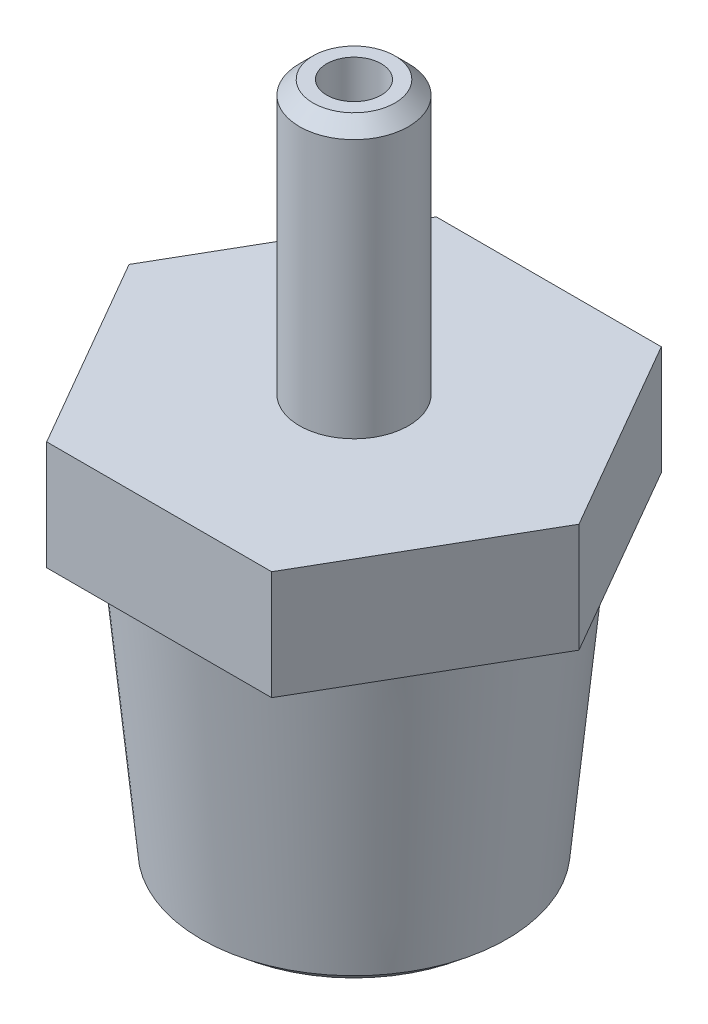
SolidWorks part; units mm, degrees
material "Brass"
ref_plane "Ground_Plane" through (0, 0, 0) normal (0, 0, 1) x (1, 0, 0)
ref_plane "VehicleCentre_Plane" through (0, 0, 0) normal (0, 1, 0) x (1, 0, 0)
ref_plane "FrontAxle_Plane" through (0, 0, 0) normal (1, 0, 0) x (0, 0, -1)
sketch "Sketch1" plane through (0, 0, 0) normal (0, 0, 1) x (1, 0, 0)
  line L0 (1, 25) -> (2, 25)
  line L1 (2, 25) -> (2, 15)
  line L2 (2, 15) -> (7, 15)
  line L3 (7, 15) -> (5.5562, 0)
  line L4 (5.5562, 0) -> (3.5562, 0)
  line L5 (3.5562, 0) -> (3.5562, 12)
  line L6 (3.5562, 12) -> (1, 12)
  line L7 (1, 12) -> (1, 25)
  line L8 (0, 0) -> (0, 25) construction
  dimension "D1" = 1
  dimension "D2" = 25
  dimension "D3" = 15
  dimension "D4" = 5.5562
  dimension "D5" = 7
  dimension "D6" = 2
  dimension "D7" = 12
  dimension "D8" = 2
revolve "Revolve1" add sketch "Sketch1" angle 360 about L8
sketch "Sketch2" plane through (0, 15, 0) normal (0, 1, 0) x (1, 0, 0)
  line L1 (-8.2489, 0) -> (-4.1244, -7.1437)
  line L2 (-4.1244, -7.1437) -> (4.1244, -7.1437)
  line L3 (4.1244, -7.1437) -> (8.2489, 0)
  line L4 (8.2489, 0) -> (4.1244, 7.1437)
  line L5 (4.1244, 7.1437) -> (-4.1244, 7.1437)
  line L6 (-4.1244, 7.1437) -> (-8.2489, 0)
  circle A0 centre (0, 0) radius 7.1437 construction
  circle A2 centre (0, 0) radius 1 construction
  circle A3 centre (0, 0) radius 1
  dimension "D1" = 14.2875
extrude "Boss-Extrude1" add sketch "Sketch2" against normal blind 4
chamfer "Chamfer1" distance 0.5 angle 45 2 edges at (0, 0, -5.5562) (0, 25, -2)
equation "\"D7@Sketch1\"=\"D3@Sketch1\"-3"
